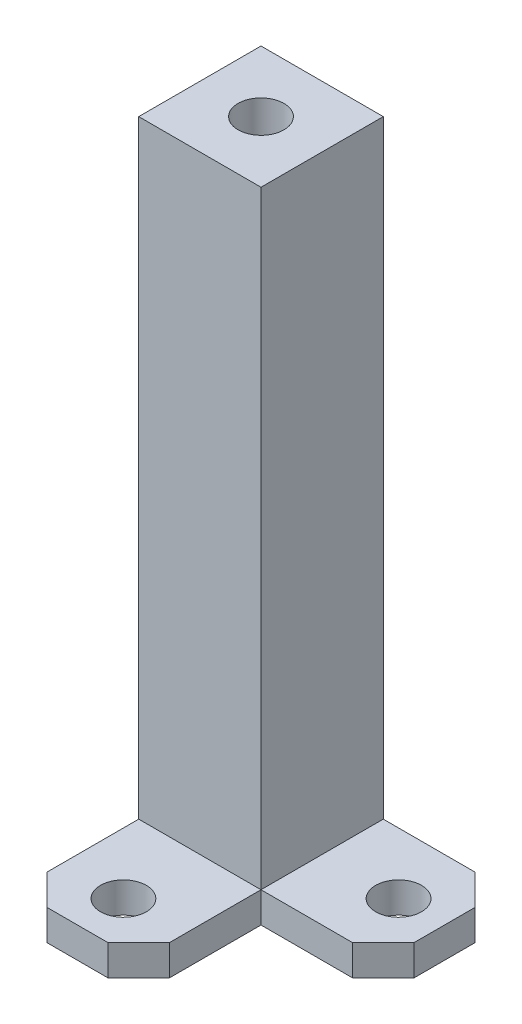
SolidWorks part; units mm, degrees
ref_plane "Front Plane" through (0, 0, 0) normal (0, 0, 1) x (1, 0, 0)
ref_plane "Top Plane" through (0, 0, 0) normal (0, 1, 0) x (1, 0, 0)
ref_plane "Right Plane" through (0, 0, 0) normal (1, 0, 0) x (0, 0, -1)
sketch "Sketch1" plane through (0, 0, 0) normal (0, 1, 0) x (1, 0, 0)
  line L1 (0, 0) -> (8, 0)
  line L2 (0, 0) -> (0, 8)
  line L3 (0, 8) -> (8, 8)
  line L4 (8, 0) -> (8, 8)
  dimension "D1" = 8
  dimension "D2" = 8
extrude "Boss-Extrude1" add sketch "Sketch1" along normal blind 41.8
sketch "Sketch2" plane through (0, 41.8, 0) normal (0, 1, 0) x (1, 0, 0)
  line L0 (4, 0) -> (4, 8) construction
  line L1 (0, 0) -> (8, 0) construction
  line L2 (8, 8) -> (0, 8) construction
  circle A0 centre (4, 4) radius 1.5
  dimension "D1" = 3
extrude "Cut-Extrude1" cut sketch "Sketch2" against normal blind 4 contours A0
sketch "Sketch3" plane through (0, 0, 0) normal (0, 1, 0) x (1, 0, 0)
  line L1 (8, 0) -> (16, 0)
  line L2 (8, 0) -> (8, 8)
  line L3 (8, 8) -> (16, 8)
  line L4 (16, 0) -> (16, 8)
  dimension "D2" = 8
  dimension "D4" = 8
extrude "Boss-Extrude2" add sketch "Sketch3" along normal blind 2
sketch "Sketch4" plane through (0, 0, 0) normal (0, 1, 0) x (1, 0, 0)
  line L1 (0, 0) -> (8, 0)
  line L2 (0, 0) -> (0, -8)
  line L3 (0, -8) -> (8, -8)
  line L4 (8, 0) -> (8, -8)
  dimension "D1" = 8
  dimension "D2" = 8
extrude "Boss-Extrude3" add sketch "Sketch4" along normal blind 2
chamfer "Chamfer1" distance 2 angle 45 4 edges at (0, 1, 8) (8, 1, 8) (16, 1, 0) (16, 1, -8)
sketch "Sketch5" plane through (0, 2, 0) normal (0, 1, 0) x (1, 0, 0)
  line L0 (4, -8) -> (4, 0) construction
  line L1 (2, -8) -> (6, -8) construction
  line L2 (0, 0) -> (8, 0) construction
  line L3 (8, 0) -> (0, 0) construction
  line L4 (8, 4) -> (16, 4) construction
  line L5 (8, 8) -> (8, 0) construction
  line L6 (16, 2) -> (16, 6) construction
  circle A0 centre (4, -5) radius 1.5
  circle A1 centre (13, 4) radius 1.5
  dimension "D1" = 3
  dimension "D3" = 3
  dimension "D2" = 5
  dimension "D4" = 5
extrude "Cut-Extrude2" cut sketch "Sketch5" against normal blind 2
